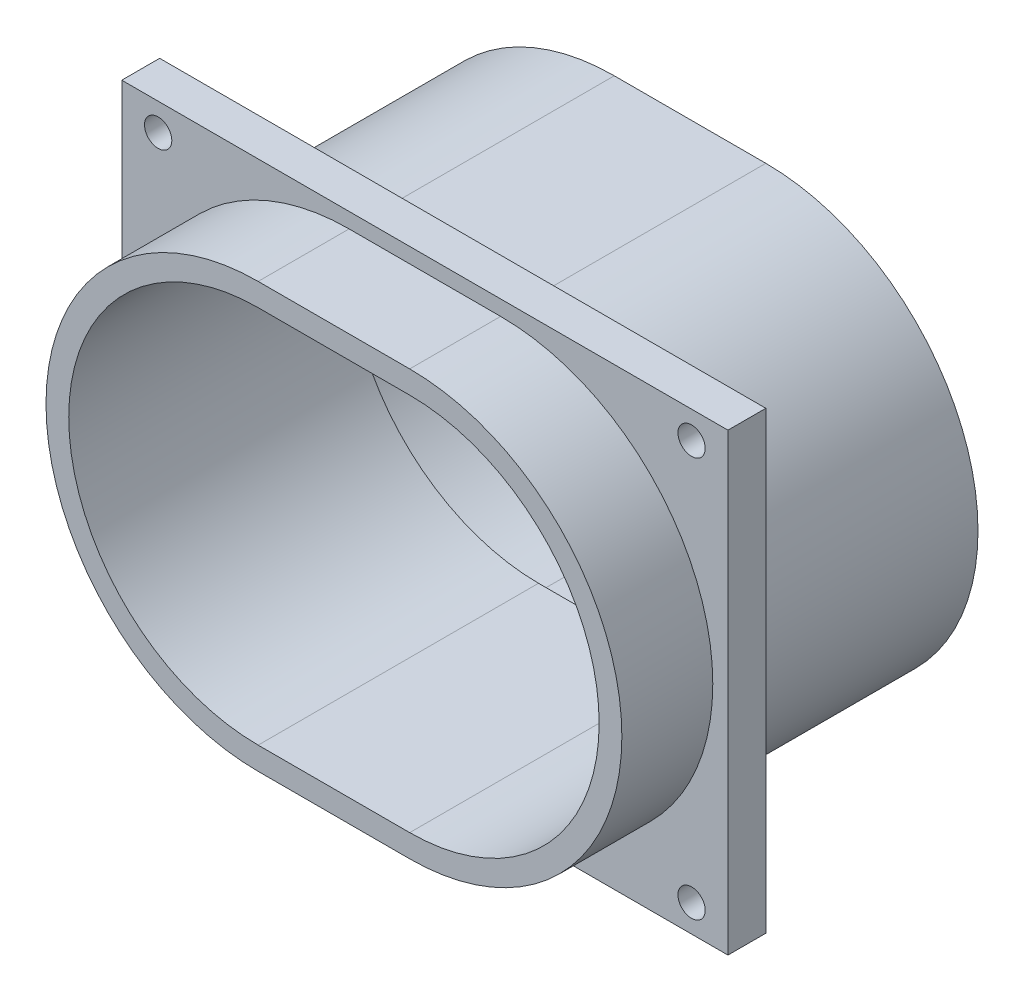
SolidWorks part; units mm, degrees
ref_plane "Front Plane" through (0, 0, 0) normal (0, 0, 1) x (1, 0, 0)
ref_plane "Top Plane" through (0, 0, 0) normal (0, 1, 0) x (1, 0, 0)
ref_plane "Right Plane" through (0, 0, 0) normal (1, 0, 0) x (0, 0, -1)
sketch "Sketch5" plane through (0, 0, 0) normal (0, 0, 1) x (1, 0, 0)
  line L1 (10, -28) -> (-10, -28)
  line L3 (10, 28) -> (-10, 28)
  line L5 (-38, 0) -> (38, 0) construction
  arc A0 (-10, 28) -> (-10, -28) centre (-10, 0) ccw
  arc A3 (10, -28) -> (10, 28) centre (10, 0) ccw
  point P0 (0, 0)
  dimension "D1" = 20
  dimension "D2" = 56
  dimension "D3" = 76
extrude "Boss-Extrude3" add sketch "Sketch5" along normal blind 12
sketch "Sketch6" plane through (0, 0, 12) normal (0, 0, 1) x (1, 0, 0)
  line L1 (10, -25) -> (-10, -25)
  line L3 (10, 25) -> (-10, 25)
  arc A0 (-10, 25) -> (-10, -25) centre (-10, 0) ccw
  arc A1 (10, -25) -> (10, 25) centre (10, 0) ccw
  point P0 (0, 0)
  dimension "D1" = 20
  dimension "D2" = 50
extrude "Cut-Extrude1" cut sketch "Sketch6" against normal blind 12
sketch "Sketch7" plane through (0, 0, 0) normal (0, 0, -1) x (-1, 0, 0)
  line L1 (40, -30) -> (-40, -30)
  line L2 (40, -30) -> (40, 30)
  line L3 (40, 30) -> (-40, 30)
  line L4 (-40, -30) -> (-40, 30)
  line L5 (40, -30) -> (25.8155, -19.3616) construction
  line L6 (40, 30) -> (25.8155, 19.3616) construction
  line L7 (10, -25) -> (-10, -25)
  line L9 (10, 25) -> (-10, 25)
  line L14 (-25.8155, 19.3616) -> (-40, 30) construction
  line L15 (-25.8155, -19.3616) -> (-40, -30) construction
  arc A0 (-10, 25) -> (-10, -25) centre (-10, 0) ccw
  arc A3 (10, -25) -> (10, 25) centre (10, 0) ccw
  point P0 (0, 0)
  point P6 (0, 0)
  dimension "D1" = 60
  dimension "D2" = 80
extrude "Boss-Extrude4" add sketch "Sketch7" along normal blind 5
sketch "Sketch9" plane through (0, 0, -5) normal (0, 0, -1) x (-1, 0, 0)
  line L0 (38, 0) -> (-38, 0) construction
  line L1 (10, -28) -> (-10, -28)
  line L3 (10, 28) -> (-10, 28)
  line L5 (10, -25) -> (-10, -25)
  line L7 (10, 25) -> (-10, 25)
  arc A0 (-10, 28) -> (-10, -28) centre (-10, 0) ccw
  arc A2 (10, -28) -> (10, 28) centre (10, 0) ccw
  arc A3 (-10, 25) -> (-10, -25) centre (-10, 0) ccw
  arc A4 (10, -25) -> (10, 25) centre (10, 0) ccw
  point P0 (0, 0)
  point P8 (0, 0)
extrude "Boss-Extrude5" add sketch "Sketch9" along normal blind 30
sketch "Sketch10" plane through (0, 0, -5) normal (0, 0, -1) x (-1, 0, 0)
  line L0 (0, 0) -> (-40, 30) construction
  line L1 (-40, 30) -> (40, -30) construction
  line L2 (40, -30) -> (40, 30) construction
  line L3 (40, 30) -> (-40, -30) construction
  circle A0 centre (-35.2, 26.4) radius 1.8
  circle A1 centre (35.2, 26.4) radius 1.8
  circle A2 centre (35.2, -26.4) radius 1.8
  circle A3 centre (-35.2, -26.4) radius 1.8
  dimension "D1" = 3.6
  dimension "D2" = 3.6
  dimension "D3" = 3.6
  dimension "D4" = 3.6
  dimension "D5" = 6
  dimension "D6" = 6
  dimension "D7" = 6
  dimension "D8" = 6
extrude "Cut-Extrude2" cut sketch "Sketch10" against normal blind 30
sketch "Sketch11" plane through (0, 0, -35) normal (0, 0, -1) x (-1, 0, 0)
  line L1 (10, -26) -> (-10, -26)
  line L3 (10, 26) -> (-10, 26)
  arc A0 (-10, 26) -> (-10, -26) centre (-10, 0) ccw
  arc A3 (10, -26) -> (10, 26) centre (10, 0) ccw
  point P0 (0, 0)
  dimension "D1" = 20
  dimension "D2" = 52
extrude "Cut-Extrude3" cut sketch "Sketch11" against normal blind 10
